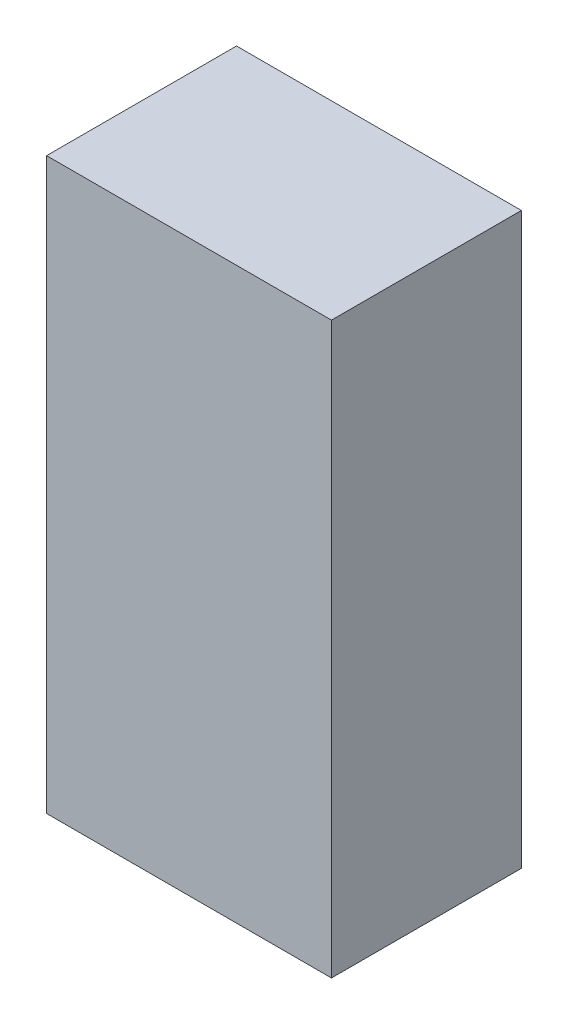
SolidWorks part; units mm, degrees
ref_plane "Front Plane" through (0, 0, 0) normal (0, 0, 1) x (1, 0, 0)
ref_plane "Top Plane" through (0, 0, 0) normal (0, 1, 0) x (1, 0, 0)
ref_plane "Right Plane" through (0, 0, 0) normal (1, 0, 0) x (0, 0, -1)
sketch "Sketch1" plane through (0, 0, 0) normal (0, 0, 1) x (1, 0, 0)
  line L1 (15, -30) -> (-15, -30)
  line L2 (15, -30) -> (15, 30)
  line L3 (15, 30) -> (-15, 30)
  line L4 (-15, -30) -> (-15, 30)
  line L5 (15, -30) -> (-15, 30) construction
  line L6 (15, 30) -> (-15, -30) construction
  point P0 (0, 0)
  dimension "D1" = 30
  dimension "D2" = 60
extrude "Boss-Extrude1" add sketch "Sketch1" along normal blind 20
scale "Scale1" bodies to scale 101 scale about centroid uniform scaling yes scale factor 0.001
